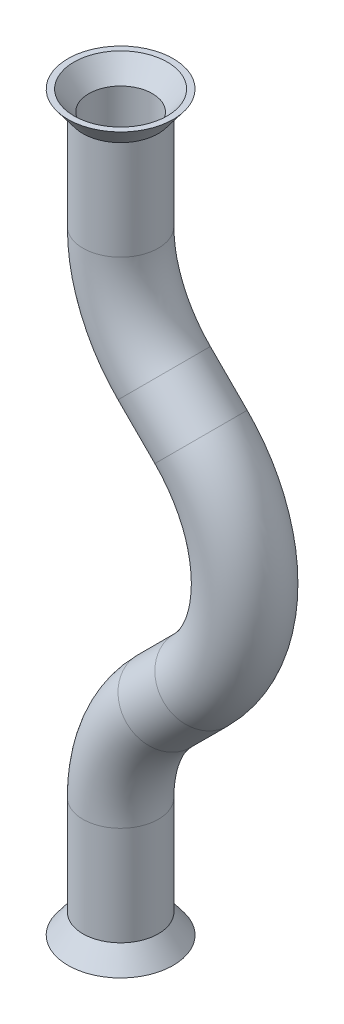
SolidWorks part; units mm, degrees
material "6061-T6 (SS)"
ref_plane "Front Plane" through (0, 0, 0) normal (0, 0, 1) x (1, 0, 0)
ref_plane "Top Plane" through (0, 0, 0) normal (0, 1, 0) x (1, 0, 0)
ref_plane "Right Plane" through (0, 0, 0) normal (1, 0, 0) x (0, 0, -1)
sketch "Sketch1" plane through (0, 0, 0) normal (0, 1, 0) x (1, 0, 0)
  circle A0 centre (0, 0) radius 4.826
  circle A1 centre (0, 0) radius 4.064
  dimension "D1" = 9.652
  dimension "D2" = 8.128
sketch "Sketch2" plane through (0, 0, 0) normal (0, 0, 1) x (1, 0, 0)
  line L0 (0, 0) -> (0, 12.7)
  line L1 (5.5796, 26.1704) -> (10.2954, 30.8862)
  line L3 (10.2954, 57.8269) -> (5.5796, 62.5427)
  line L4 (0, 76.0131) -> (0, 88.7131)
  arc A0 (0, 12.7) -> (5.5796, 26.1704) centre (19.05, 12.7) cw
  arc A1 (10.2954, 30.8862) -> (10.2954, 57.8269) centre (-3.175, 44.3565) ccw
  arc A3 (5.5796, 62.5427) -> (0, 76.0131) centre (19.05, 76.0131) cw
  point P26 (15.875, 44.3565)
  dimension "D1" = 15.875
  dimension "D2" = 135
  dimension "D3" = 19.05
  dimension "D6" = 12.7
sweep "Sweep1" add profiles "Sketch1" path "Sketch2"
sketch "Sketch3" plane through (0, 0, 0) normal (0, -1, 0) x (1, 0, 0)
  circle A0 centre (0, 0) radius 4.826
  circle A1 centre (0, 0) radius 4.826 construction
extrude "Boss-Extrude1" add sketch "Sketch3" along normal blind 2.54 draft 37 draft outward yes
sketch "Sketch4" plane through (0, -2.54, 0) normal (0, -1, 0) x (1, 0, 0)
  line L0 (-4.826, 0) -> (-4.064, 0) construction
  line L1 (-5.978, 0) -> (-6.74, 0) construction
  circle A0 centre (0, 0) radius 5.978
  circle A1 centre (0, 0) radius 4.826 construction
  circle A2 centre (0, 0) radius 4.064 construction
  circle A3 centre (0, 0) radius 6.74 construction
extrude "Cut-Extrude1" cut sketch "Sketch4" against normal through all draft 37
sketch "Sketch5" plane through (0, 88.7131, 0) normal (0, 1, 0) x (0, 0, -1)
  circle A1 centre (0, 0) radius 4.826
  circle A4 centre (0, 0) radius 4.826 construction
extrude "Boss-Extrude2" add sketch "Sketch5" along normal blind 2.54 draft 37 draft outward yes
sketch "Sketch6" plane through (0, 91.2531, 0) normal (0, 1, 0) x (0, 0, -1)
  line L0 (-5.978, 0) -> (-6.74, 0) construction
  circle A0 centre (0, 0) radius 5.978
  circle A1 centre (0, 0) radius 6.74 construction
  dimension "D1" = 0.762
extrude "Cut-Extrude2" cut sketch "Sketch6" against normal through all draft 37
